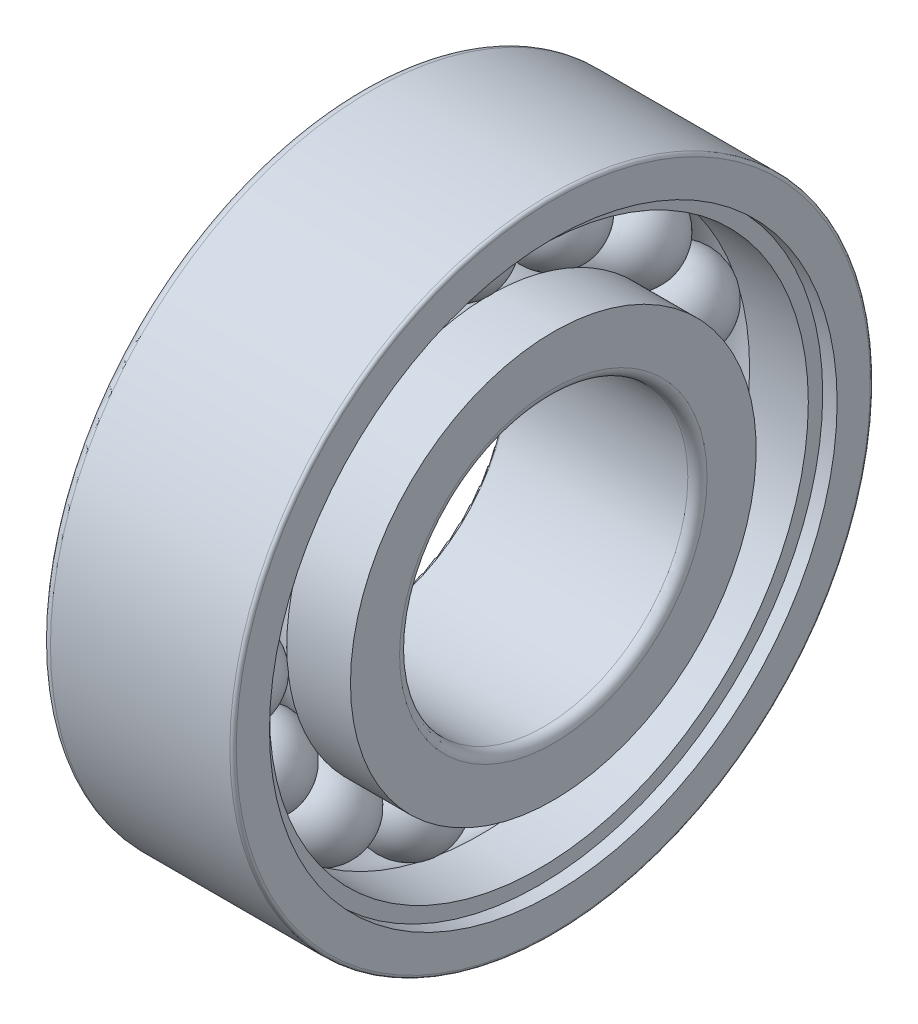
SolidWorks part; units mm, degrees
ref_plane "Front" through (0, 0, 0) normal (0, 0, 1) x (1, 0, 0)
ref_plane "Top" through (0, 0, 0) normal (0, 1, 0) x (1, 0, 0)
ref_plane "Right" through (0, 0, 0) normal (1, 0, 0) x (0, 0, -1)
sketch "Sketch1" plane through (0, 0, 0) normal (0, 0, 1) x (1, 0, 0)
  line L0 (-3.0919, 0) -> (2.899, 0) construction
  line L1 (-3.0919, 7.25) -> (2.899, 7.25) construction
  line L2 (-1.375, 7.25) -> (1.375, 7.25)
  arc A0 (-1.375, 7.25) -> (1.375, 7.25) centre (0, 7.25) ccw
  dimension "R" = 1.375
  dimension "D1" = 7.25
revolve "Revolve1" add sketch "Sketch1" angle 360 about L1
sketch "Sketch2" plane through (0, 0, 0) normal (0, 0, 1) x (1, 0, 0)
  line L0 (-3, 6.3333) -> (-1.0114, 6.3333)
  line L1 (3, 6.3333) -> (3, 4.5)
  line L2 (3, 4.5) -> (-3, 4.5)
  line L3 (-3, 4.5) -> (-3, 6.3333)
  line L4 (-2.9924, 0) -> (3.9982, 0) construction
  line L5 (-1.8743, 7.25) -> (3.1755, 7.25) construction
  line L7 (1.0114, 6.3333) -> (3, 6.3333)
  line L8 (-3, 6.2861) -> (-3, 1.454) construction
  arc A0 (-1.0114, 6.3333) -> (1.0114, 6.3333) centre (0, 7.25) ccw
  dimension "D1" = 7.25
  dimension "B" = 6
  dimension "D2" = 1.365
  dimension "d" = 9
  dimension "D3" = 12.6667
  dimension "T" = 6
  dimension "D6" = 3
revolve "Revolve2" add sketch "Sketch2" angle 360 about L4
sketch "Sketch3" plane through (0, 0, 0) normal (0, 0, 1) x (1, 0, 0)
  line L0 (-3, 8.1667) -> (-3, 10)
  line L1 (-3, 10) -> (3, 10)
  line L2 (3, 10) -> (3, 8.8617)
  line L3 (2.55, 8.4117) -> (0.7168, 8.4117)
  line L4 (-2.9924, 0) -> (3.4329, 0) construction
  line L6 (-1.7375, 7.25) -> (2.2712, 7.25) construction
  line L7 (-1.0114, 8.1667) -> (-3, 8.1667)
  line L8 (2.55, 8.4117) -> (2.55, 8.8617)
  line L9 (2.55, 8.8617) -> (3, 8.8617)
  arc A0 (0.7168, 8.4117) -> (-1.0114, 8.1667) centre (0, 7.25) ccw
  dimension "D1" = 7.25
  dimension "D4" = 1.365
  dimension "B" = 6
  dimension "DD" = 20
  dimension "D3" = 16.8233
  dimension "D5" = 16.3333
  dimension "D6" = 0.45
  dimension "D7" = 0.45
  dimension "D2" = 3
revolve "Revolve3" add sketch "Sketch3" angle 360 about L4
pattern_circular "Circular-Pattern1" count 15 over 360 about axis through (0, 0, 0) along (1, 0, 0) of "Revolve1"
fillet "Fillet1" radius 0.3 2 edges at (3, 0, 4.5) (-3, 0, 10)
fillet "Fillet2" radius 0.1 2 edges at (3, 0, 10) (-3, 0, 4.5)
equation "\"R@Sketch1\" =  ( \"DD@Sketch3\" - \"d@Sketch2\" )  / 8"
equation "\"D1@Sketch1\"=(\"d@Sketch2\"+\"DD@Sketch3\")/4"
equation "\"D1@Sketch2\"=(\"d@Sketch2\"+\"DD@Sketch3\")/4"
equation "\"D3@Sketch2\" =  \"d@Sketch2\"+  ( \"DD@Sketch3\" - \"d@Sketch2\" )  /3"
equation "\"D2@Sketch2\" =  ( \"DD@Sketch3\" - \"d@Sketch2\" )  / 8 - 0.01"
equation "\"D6@Sketch2\" = \"B@Sketch2\" / 2"
equation "\"B@Sketch3\" = \"B@Sketch2\""
equation "\"D2@Sketch3\" = \"B@Sketch3\" / 2"
equation "\"D1@Sketch3\"=(\"d@Sketch2\"+\"DD@Sketch3\")/4"
equation "\"D3@Sketch3\" = (  \"DD@Sketch3\" -  (\"DD@Sketch3\" - \"d@Sketch2\"  )  / 3 )  * 1.03"
equation "\"D5@Sketch3\" = \"DD@Sketch3\" -  (  \"DD@Sketch3\" - \"d@Sketch2\")  / 3"
equation "\"D6@Sketch3\" = \"d@Sketch2\" / 20"
equation "\"D7@Sketch3\"=\"D6@Sketch3\""
equation "\"D4@Sketch3\"=(\"DD@Sketch3\"-\"d@Sketch2\")/8-0.01"
equation "\"m@Circular-Pattern1\" = int( 3.14159265 / atn(\"R@Sketch1\" / sqr((\"d@Sketch2\"+\"DD@Sketch3\")/4 * (\"d@Sketch2\"+\"DD@Sketch3\")/4 - \"R@Sketch1\" *  \"R@Sketch1\")))-1"
